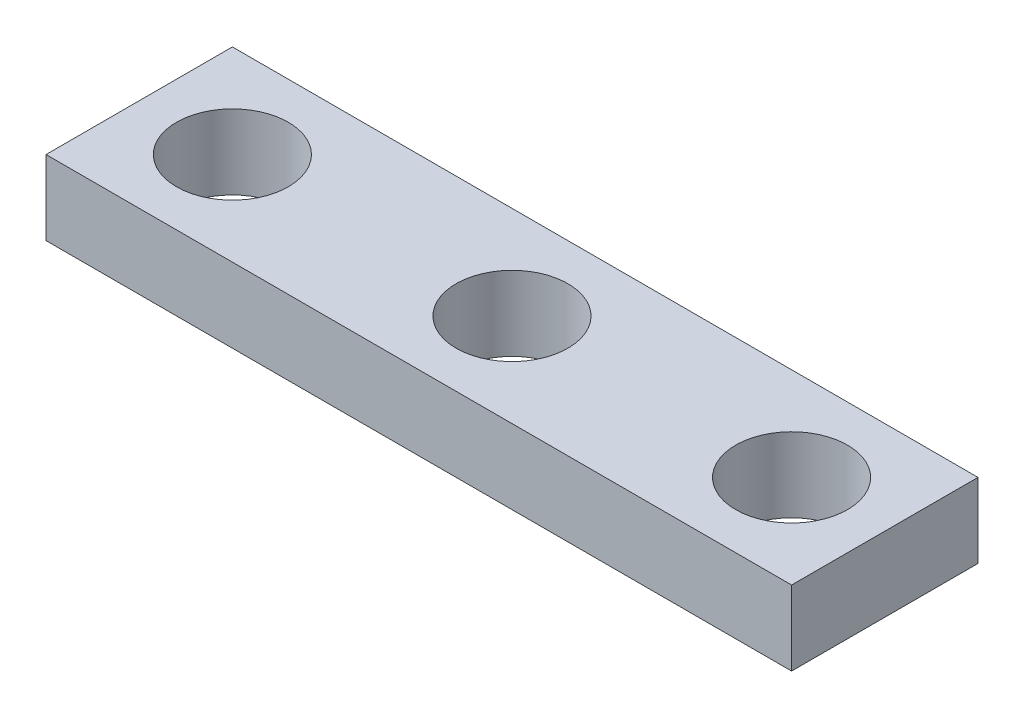
SolidWorks part; units mm, degrees
ref_plane "Front Plane" through (0, 0, 0) normal (0, 0, 1) x (1, 0, 0)
ref_plane "Top Plane" through (0, 0, 0) normal (0, 1, 0) x (1, 0, 0)
ref_plane "Right Plane" through (0, 0, 0) normal (1, 0, 0) x (0, 0, -1)
sketch "Sketch1" plane through (0, 0, 0) normal (0, 1, 0) x (1, 0, 0)
  line L0 (-7.5, 0) -> (7.5, 0) construction
  line L1 (-10, -2.5) -> (10, -2.5)
  line L2 (-10, -2.5) -> (-10, 2.5)
  line L3 (-10, 2.5) -> (10, 2.5)
  line L4 (10, -2.5) -> (10, 2.5)
  line L5 (-10, -2.5) -> (10, 2.5) construction
  line L6 (-10, 2.5) -> (10, -2.5) construction
  circle A0 centre (-7.5, 0) radius 1.5
  circle A1 centre (7.5, 0) radius 1.5
  circle A2 centre (0, 0) radius 1.5
  point P0 (0, 0)
  point P12 (0, 0)
  dimension "D4" = 3
  dimension "D5" = 3
  dimension "D1" = 5
  dimension "D2" = 20
  dimension "D3" = 15
extrude "Boss-Extrude1" add sketch "Sketch1" along normal blind 2
